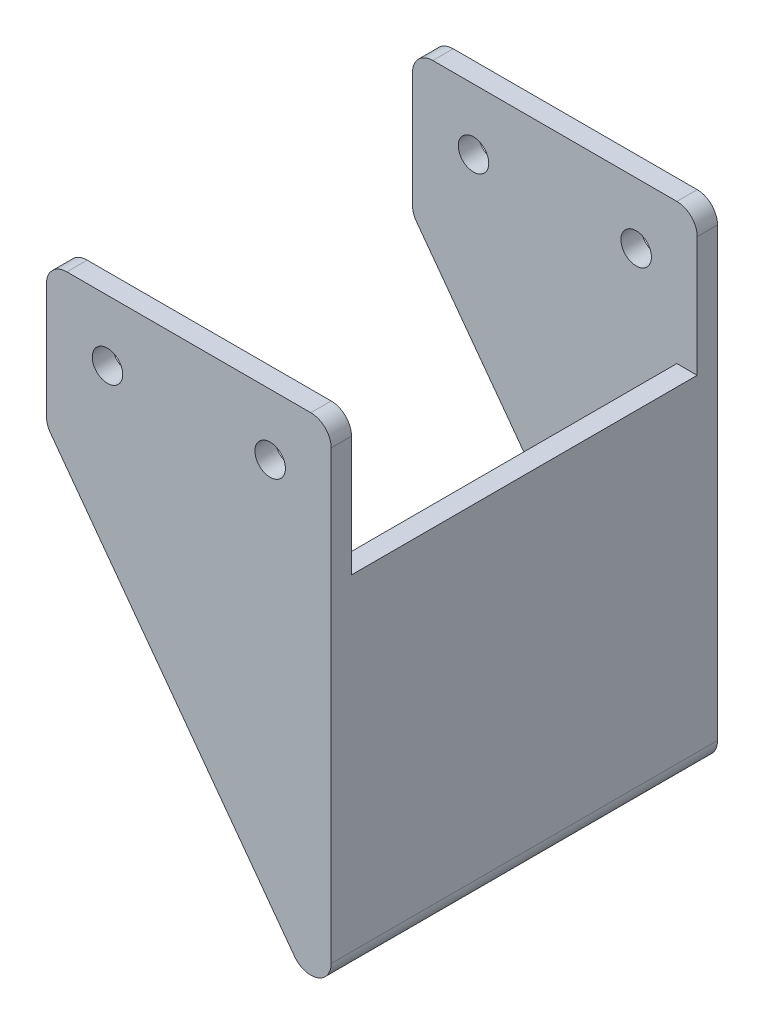
SolidWorks part; units mm, degrees
ref_plane "Front Plane" through (0, 0, 0) normal (0, 0, 1) x (1, 0, 0)
ref_plane "Top Plane" through (0, 0, 0) normal (0, 1, 0) x (1, 0, 0)
ref_plane "Right Plane" through (0, 0, 0) normal (1, 0, 0) x (0, 0, -1)
sketch "Sketch1" plane through (0, 0, 0) normal (0, 0, 1) x (1, 0, 0)
  line L0 (0, -1) -> (0, -22.9571)
  line L1 (-1.8051, -23.5503) -> (-13.8051, -7.2646)
  line L2 (-14, -6.6714) -> (-14, -1)
  line L3 (-13, 0) -> (-1, 0)
  arc A0 (0, -22.9571) -> (-1.8051, -23.5503) centre (-1, -22.9571) cw
  arc A1 (-13.8051, -7.2646) -> (-14, -6.6714) centre (-13, -6.6714) cw
  arc A2 (-14, -1) -> (-13, 0) centre (-13, -1) cw
  arc A3 (0, -1) -> (-1, 0) centre (-1, -1) ccw
  circle A4 centre (-11, -3) radius 0.75
  circle A5 centre (-3, -3) radius 0.75
  point P7 (0, -26)
  point P10 (-14, -7)
  point P13 (-14, 0)
  point P16 (0, 0)
  dimension "D4" = 1
  dimension "D5" = 1
  dimension "D6" = 8
  dimension "D8" = 1.5
  dimension "D9" = 1.5
  dimension "D1" = 26
  dimension "D2" = 14
  dimension "D3" = 7
  dimension "D7" = 3
  dimension "D10" = 3
extrude "Boss-Extrude1" add sketch "Sketch1" along normal mid plane 19
sketch "Sketch2" plane through (0, 0, 0) normal (0, 0, 1) x (1, 0, 0)
  line L0 (-1, -28.3486) -> (-1, -6.9071)
  line L1 (-1, -6.9071) -> (7.9264, -6.9071)
  line L2 (7.9264, -6.9071) -> (7.2949, 4.747)
  line L3 (7.2949, 4.747) -> (-21.6673, 6.8711)
  line L4 (-21.6673, 6.8711) -> (-20.0347, -23.2588)
  line L5 (-20.0347, -23.2588) -> (-1, -28.3486)
  line L6 (0, -22.9571) -> (0, -1) construction
  arc A0 (-1.8051, -23.5503) -> (0, -22.9571) centre (-1, -22.9571) ccw construction
  point P9 (-0.6878, -23.9071)
  dimension "D1" = 17
  dimension "D2" = 1
extrude "Cut-Extrude1" cut sketch "Sketch2" against normal mid plane 17
sketch "Sketch3" plane through (0, 0, 9.5) normal (0, 0, 1) x (1, 0, 0)
  circle A0 centre (-3, -3) radius 0.75
